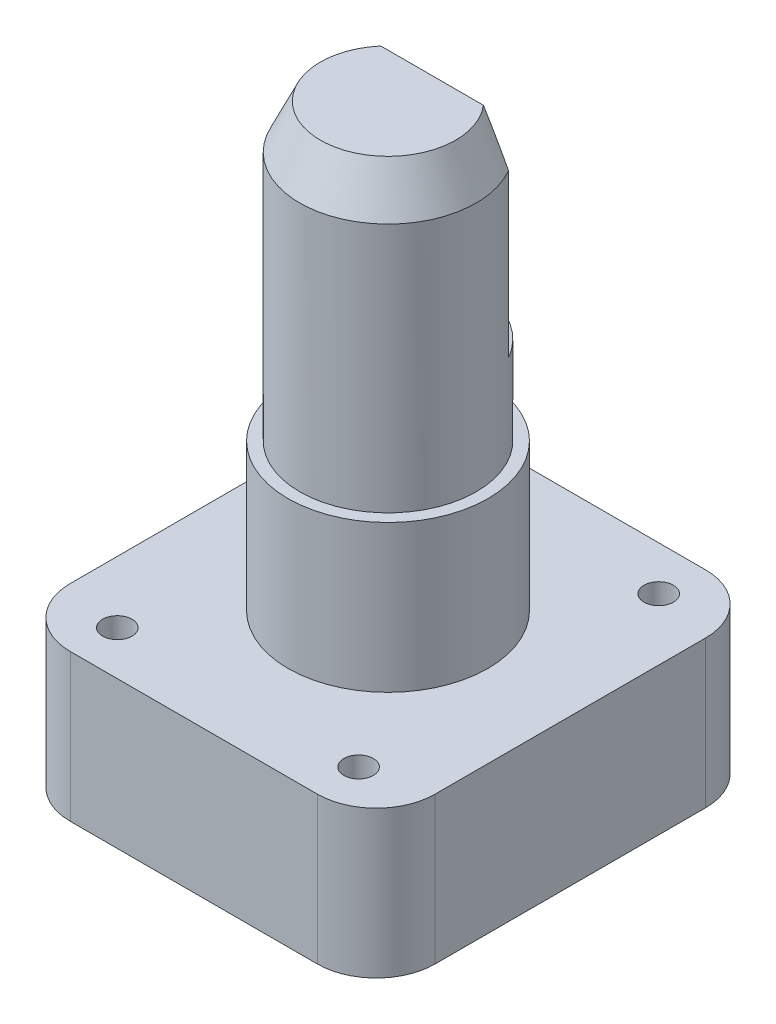
SolidWorks part; units mm, degrees
ref_plane "Front Plane" through (0, 0, 0) normal (0, 0, 1) x (1, 0, 0)
ref_plane "Top Plane" through (0, 0, 0) normal (0, 1, 0) x (1, 0, 0)
ref_plane "Right Plane" through (0, 0, 0) normal (1, 0, 0) x (0, 0, -1)
sketch "Sketch1" plane through (0, 0, 0) normal (0, 1, 0) x (1, 0, 0)
  line L1 (-6.2, 6.6) -> (6.2, 6.6)
  line L2 (-6.2, 6.6) -> (-6.2, -6.6)
  line L3 (-6.2, -6.6) -> (6.2, -6.6)
  line L4 (6.2, 6.6) -> (6.2, -6.6)
  point P4 (6.2, 0)
  point P6 (0, 6.6)
  dimension "D1" = 12.4
  dimension "D2" = 13.2
extrude "Boss-Extrude1" add sketch "Sketch1" along normal blind 5
fillet "Fillet1" radius 2 4 edges at (-6.2, 2.5, -6.6) (-6.2, 2.5, 6.6) (6.2, 2.5, -6.6) (6.2, 2.5, 6.6)
sketch "Sketch2" plane through (0, 5, 0) normal (0, 1, 0) x (1, 0, 0)
  circle A0 centre (0, 0) radius 3.4
  dimension "D1" = 6.8
extrude "Boss-Extrude2" add sketch "Sketch2" along normal blind 5
sketch "Sketch3" plane through (0, 10, 0) normal (0, 1, 0) x (1, 0, 0)
  circle A0 centre (0, 0) radius 3
  dimension "D1" = 6
extrude "Boss-Extrude3" add sketch "Sketch3" along normal blind 10
chamfer "Chamfer1" distance 1.5 angle 25 1 edges at (0, 20, 3)
sketch "Sketch4" plane through (0, 5, 0) normal (0, 1, 0) x (1, 0, 0)
  line L0 (-4.1, -5.1) -> (4.1, 5.1) construction
  line L1 (-4.1, 5.1) -> (4.1, -5.1) construction
  circle A0 centre (4.1, -5.1) radius 0.5
  circle A1 centre (-4.1, -5.1) radius 0.5
  circle A2 centre (-4.1, 5.1) radius 0.5
  circle A3 centre (4.1, 5.1) radius 0.5
  point P8 (0, 0)
  dimension "D1" = 1
  dimension "D2" = 1
  dimension "D3" = 1
  dimension "D4" = 1
  dimension "D5" = 10.2
  dimension "D6" = 8.2
extrude "Cut-Extrude1" cut sketch "Sketch4" against normal through all
sketch "Sketch5" plane through (0, 20, 0) normal (0, 1, 0) x (1, 0, 0)
  line L0 (0, -3) -> (4.4161, -3) construction
  line L1 (-3, 1.5) -> (3.0512, 1.5)
  line L2 (-3, 1.5) -> (-3, 3)
  line L3 (-3, 3) -> (3.0512, 3)
  line L4 (3.0512, 1.5) -> (3.0512, 3)
  circle A0 centre (0, 0) radius 3.4 construction
  circle A1 centre (0, 0) radius 3.4 construction
  circle A2 centre (0, 0) radius 3 construction
  circle A4 centre (0, 0) radius 3 construction
  dimension "D1" = 4.5
extrude "Cut-Extrude2" cut sketch "Sketch5" against normal blind 7
equation "\"D2@Sketch4\"=\"D1@Sketch4\""
equation "\"D3@Sketch4\"=\"D1@Sketch4\""
equation "\"D4@Sketch4\"=\"D1@Sketch4\""
